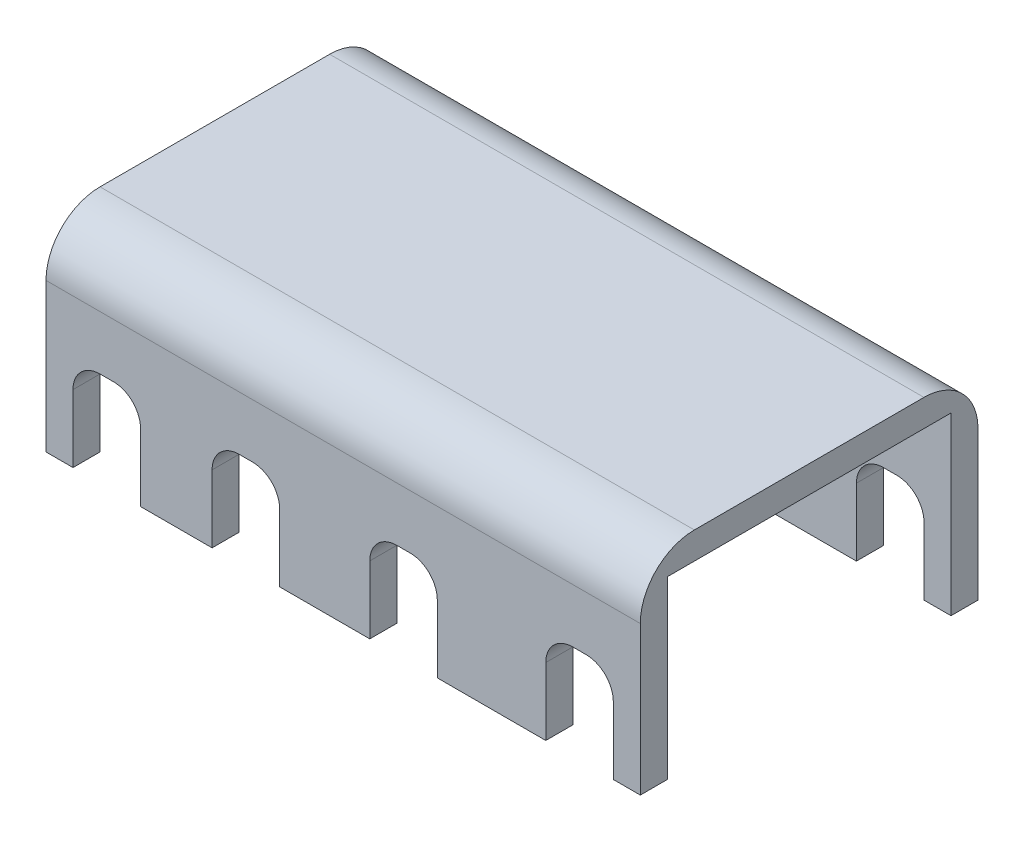
SolidWorks part; units mm, degrees
ref_plane "Plano frontal" through (0, 0, 0) normal (0, 0, 1) x (1, 0, 0)
ref_plane "Plano superior" through (0, 0, 0) normal (0, 1, 0) x (1, 0, 0)
ref_plane "Plano direito" through (0, 0, 0) normal (1, 0, 0) x (0, 0, -1)
sketch "Esboço1" plane through (0, 0, 0) normal (0, 1, 0) x (1, 0, 0)
  line L1 (-22, -12.5) -> (22, -12.5)
  line L2 (-22, -12.5) -> (-22, 12.5)
  line L3 (-22, 12.5) -> (22, 12.5)
  line L4 (22, -12.5) -> (22, 12.5)
  line L5 (-22, -12.5) -> (22, 12.5) construction
  line L6 (-22, 12.5) -> (22, -12.5) construction
  point P0 (0, 0)
  dimension "D1" = 44
  dimension "D2" = 25
extrude "Ressalto-extrusão1" add sketch "Esboço1" along normal mid plane 15
shell "Casca1" thickness 2
sketch "Esboço2" plane through (0, 0, 12.5) normal (0, 0, 1) x (1, 0, 0)
  line L0 (22, 7.5) -> (22, -7.5) construction
  line L5 (-9.7033, -14.5) -> (-4.7033, -14.5)
  line L6 (-9.7033, -14.5) -> (-9.7033, -0.5)
  line L7 (-22, -7.5) -> (22, -7.5) construction
  line L8 (-20, -14.5) -> (-15, -14.5)
  line L9 (-20, -14.5) -> (-20, -0.5)
  line L10 (-20, -0.5) -> (-15, -0.5)
  line L11 (-15, -14.5) -> (-15, -0.5)
  line L12 (-20, -14.5) -> (-15, -0.5) construction
  line L13 (-20, -0.5) -> (-15, -14.5) construction
  line L14 (-22, 7.5) -> (-22, -7.5) construction
  line L15 (-9.7033, -0.5) -> (-4.7033, -0.5)
  line L16 (-4.7033, -14.5) -> (-4.7033, -0.5)
  line L17 (-9.7033, -14.5) -> (-4.7033, -0.5) construction
  line L18 (-9.7033, -0.5) -> (-4.7033, -14.5) construction
  line L19 (1.9702, -14.5) -> (6.9702, -14.5)
  line L20 (1.9702, -14.5) -> (1.9702, -0.5)
  line L21 (1.9702, -0.5) -> (6.9702, -0.5)
  line L22 (6.9702, -14.5) -> (6.9702, -0.5)
  line L23 (1.9702, -14.5) -> (6.9702, -0.5) construction
  line L24 (1.9702, -0.5) -> (6.9702, -14.5) construction
  line L25 (15, -14.5) -> (20, -14.5)
  line L26 (15, -14.5) -> (15, -0.5)
  line L27 (15, -0.5) -> (20, -0.5)
  line L28 (20, -14.5) -> (20, -0.5)
  line L29 (15, -14.5) -> (20, -0.5) construction
  line L30 (15, -0.5) -> (20, -14.5) construction
  point P0 (-17.5, -7.5)
  point P9 (-7.2033, -7.5)
  point P14 (4.4702, -7.5)
  point P19 (17.5, -7.5)
  dimension "D2" = 5
  dimension "D3" = 7
  dimension "D1" = 2
  dimension "D4" = 2
extrude "Corte-extrusão1" cut sketch "Esboço2" against normal through all
fillet "Filete1" radius 2 16 edges at (15, -0.5, 11.5) (15, -0.5, -11.5) (20, -0.5, 11.5) (20, -0.5, -11.5) (1.9702, -0.5, 11.5) (1.9702, -0.5, -11.5) (6.9702, -0.5, 11.5) (6.9702, -0.5, -11.5) (-9.7033, -0.5, 11.5) (-9.7033, -0.5, -11.5) (-4.7033, -0.5, 11.5) (-4.7033, -0.5, -11.5) (-15, -0.5, 11.5) (-15, -0.5, -11.5) (-20, -0.5, -11.5) (-20, -0.5, 11.5)
fillet "Filete2" radius 4 2 edges at (0, 7.5, -12.5) (0, 7.5, 12.5)
